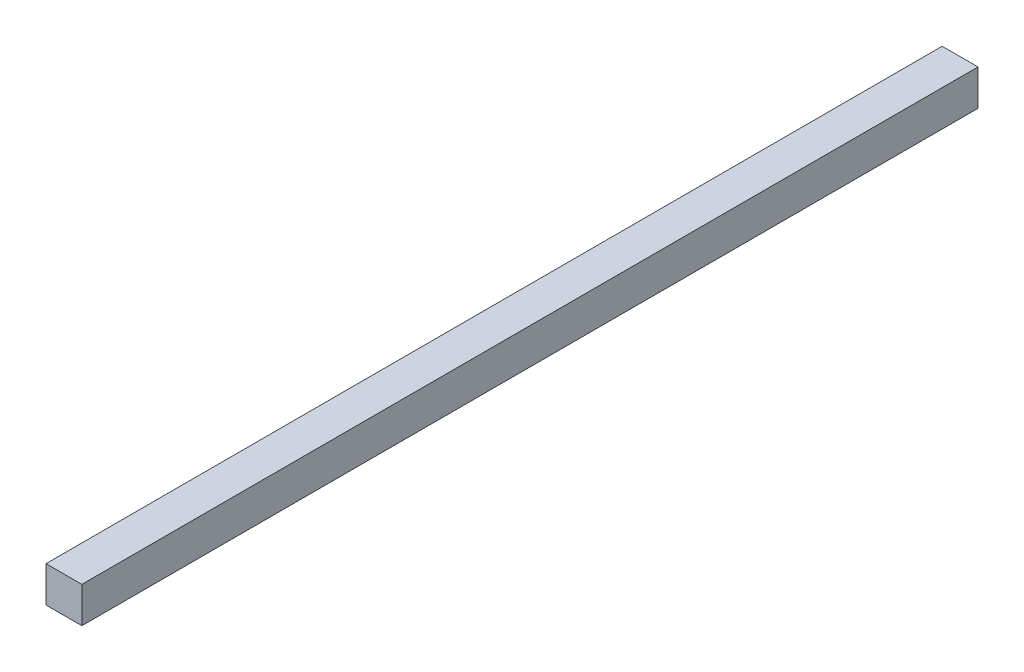
SolidWorks part; units mm, degrees
ref_plane "前视基准面" through (0, 0, 0) normal (0, 0, 1) x (1, 0, 0)
ref_plane "上视基准面" through (0, 0, 0) normal (0, 1, 0) x (1, 0, 0)
ref_plane "右视基准面" through (0, 0, 0) normal (1, 0, 0) x (0, 0, -1)
sketch "草图1" plane through (0, 0, 0) normal (0, 0, 1) x (1, 0, 0)
  line L2 (4, -4) -> (-4, -4)
  line L3 (4, -4) -> (4, 4)
  line L4 (4, 4) -> (-4, 4)
  line L5 (-4, -4) -> (-4, 4)
  line L6 (4, -4) -> (-4, 4) construction
  line L7 (4, 4) -> (-4, -4) construction
  point P1 (0, 0)
  dimension "D1" = 8
  dimension "D2" = 8
extrude "凸台-拉伸1" add sketch "草图1" along normal blind 200
